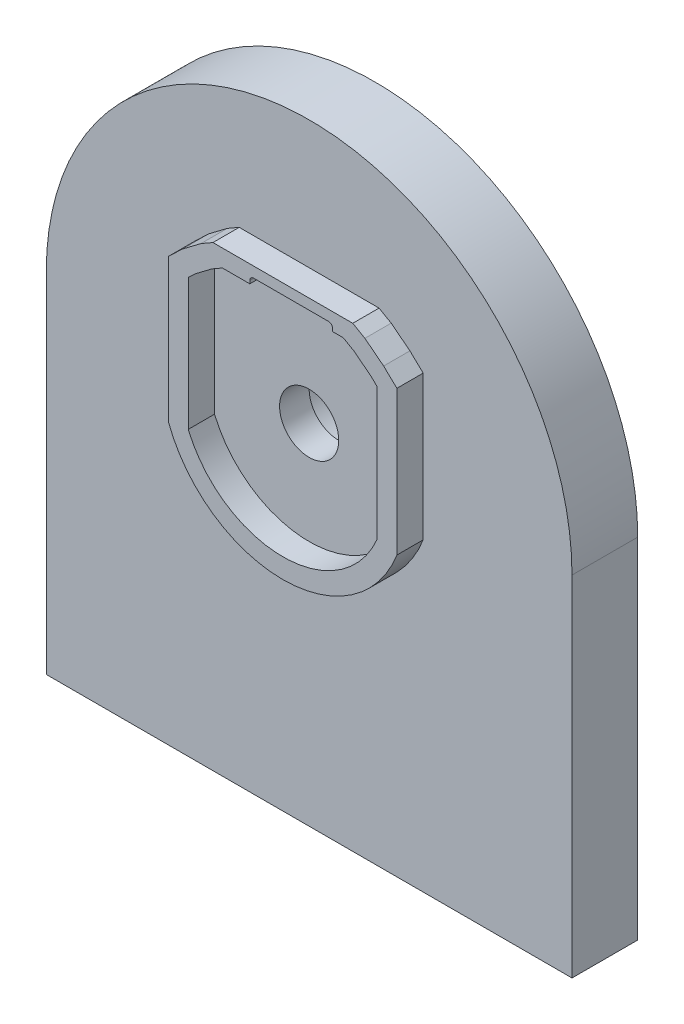
SolidWorks part; units mm, degrees
ref_plane "Front Plane" through (0, 0, 0) normal (0, 0, 1) x (1, 0, 0)
ref_plane "Top Plane" through (0, 0, 0) normal (0, 1, 0) x (1, 0, 0)
ref_plane "Right Plane" through (0, 0, 0) normal (1, 0, 0) x (0, 0, -1)
sketch "Sketch1" plane through (0, 0, 0) normal (0, 0, 1) x (1, 0, 0)
  line L1 (-40, -25) -> (40, -25)
  line L2 (-40, -25) -> (-40, 25)
  line L3 (-40, 25) -> (40, 25)
  line L4 (40, -25) -> (40, 25)
  line L5 (-40, -25) -> (40, 25) construction
  line L6 (-40, 25) -> (40, -25) construction
  point P0 (0, 0)
  dimension "D1" = 80
  dimension "D2" = 50
sketch "Sketch6" plane through (0, 0, 0) normal (0, 0, 1) x (1, 0, 0)
  line L1 (40, -53.1) -> (-40, -53.1)
  line L2 (40, -53.1) -> (40, 53.1)
  line L3 (40, 53.1) -> (-40, 53.1)
  line L4 (-40, -53.1) -> (-40, 53.1)
  line L5 (40, -53.1) -> (-40, 53.1) construction
  line L6 (40, 53.1) -> (-40, -53.1) construction
  point P0 (0, 0)
  point P8 (0, 0)
  point P9 (0, 0)
  point P10 (0, 0)
  dimension "D1" = 80
  dimension "D2" = 106.2
extrude "Boss-Extrude3" add sketch "Sketch6" along normal mid plane 10
sketch "Sketch3" plane through (0, 0, 5) normal (0, 0, 1) x (1, 0, 0)
  line L0 (-14.3953, -5.9991) -> (-14.3953, 14.0234)
  line L1 (-14.3953, 14.0234) -> (-13.3642, 15.0075)
  line L2 (-10.8024, 16.9451) -> (-13.3642, 15.0075)
  line L3 (-10.8024, 16.9451) -> (-9.2024, 17.8657)
  line L4 (-9.2024, 17.8657) -> (-5.0253, 17.8657)
  line L5 (-5.0253, 17.8657) -> (-5.0253, 18.3079)
  line L6 (-4.4301, 18.9031) -> (6.9701, 18.9031)
  line L7 (7.5653, 18.3079) -> (7.5653, 17.8657)
  line L8 (7.5653, 17.8657) -> (9.2024, 17.8657)
  line L9 (9.2024, 17.8657) -> (10.8031, 16.9447)
  line L10 (10.8031, 16.9447) -> (13.371, 14.9429)
  line L11 (13.371, 14.9429) -> (14.3516, 14.0055)
  line L12 (14.3516, 14.0055) -> (14.3516, -6.1027)
  line L13 (-17.3953, -6.5718) -> (-17.3953, 15.3072)
  line L14 (-17.3953, 15.3072) -> (-15.3111, 17.2964)
  line L15 (-12.4619, 19.4514) -> (-15.3111, 17.2964)
  line L16 (-12.4619, 19.4514) -> (-10.6394, 20.5)
  line L17 (10.6394, 20.5) -> (12.4815, 19.4401)
  line L18 (12.4815, 19.4401) -> (15.3347, 17.2159)
  line L19 (15.3347, 17.2159) -> (17.3516, 15.288)
  line L20 (17.3516, 15.288) -> (17.3516, -6.6862)
  line L21 (-10.6394, 20.5) -> (10.6394, 20.5)
  arc A0 (-5.0253, 18.3079) -> (-4.4301, 18.9031) centre (-4.4301, 18.3079) cw
  arc A1 (6.9701, 18.9031) -> (7.5653, 18.3079) centre (6.9701, 18.3079) cw
  arc A2 (-14.3953, -5.9991) -> (14.3516, -6.1027) centre (0, 0) ccw
  arc A3 (-17.3953, -6.5718) -> (17.3516, -6.6862) centre (0, 0) ccw
  dimension "D1" = 15.5953
  dimension "D9" = 0.5952
  dimension "D16" = 0.5952
  dimension "D2" = 5.9991
  dimension "D3" = 20.0224
  dimension "D4" = 20.1082
  dimension "D5" = 1.3566
  dimension "D6" = 3.256
  dimension "D7" = 1.8467
  dimension "D8" = 1.6371
  dimension "D10" = 0.4422
  dimension "D11" = 11.4002
  dimension "D12" = 1.4253
  dimension "D13" = 3.212
  dimension "D14" = 1.846
  dimension "D15" = 4.1771
  dimension "D17" = 0.4422
  dimension "D18" = 0.9373
  dimension "D19" = 2.0018
  dimension "D20" = 0.921
  dimension "D21" = 0.9206
  dimension "D22" = 1.9376
  dimension "D23" = 2.8811
  dimension "D24" = 2.7902
  dimension "D25" = 3.6176
  dimension "D26" = 2.1253
  dimension "D27" = 3.5724
  dimension "D28" = 2.1026
  dimension "D29" = 21.2787
  dimension "D30" = 1.5969
  dimension "D31" = 21.879
  dimension "D32" = 21.9742
extrude "Boss-Extrude2" add sketch "Sketch3" along normal blind 4
sketch "Sketch4" plane through (0, 0, 5) normal (0, 0, 1) x (1, 0, 0)
  line L1 (3.6373, 0) -> (1.8187, 3.15) construction
  line L2 (1.8187, 3.15) -> (-1.8187, 3.15) construction
  line L3 (-1.8187, 3.15) -> (-3.6373, 0) construction
  line L4 (-3.6373, 0) -> (-1.8187, -3.15) construction
  line L5 (-1.8187, -3.15) -> (1.8187, -3.15) construction
  line L6 (1.8187, -3.15) -> (3.6373, 0) construction
  circle A0 centre (0, 0) radius 3.15 construction
  circle A1 centre (0, 0) radius 4.5
  dimension "D2" = 9
  dimension "D1" = 6.3
extrude "Cut-Extrude2" cut sketch "Sketch4" against normal up to next
sketch "Sketch7" plane through (0, 0, -5) normal (0, 0, -1) x (-1, 0, 0)
  circle A0 centre (0, 0) radius 7.75
  point P3 (0, 0)
  dimension "D1" = 15.5
extrude "Cut-Extrude3" cut sketch "Sketch7" against normal blind 5.5
sketch "Sketch8" plane through (0, 0, 0) normal (0, 0, 1) x (1, 0, 0)
  line L0 (-40, 53.1) -> (-40, -53.1) construction
  line L1 (40, -53.1) -> (40, 53.1) construction
  line L2 (-40, 0) -> (-40, 53.1)
  line L3 (-40, 53.1) -> (40, 53.1)
  line L4 (40, 53.1) -> (40, 0)
  arc A0 (-40, 0) -> (40, 0) centre (0, 0) cw
extrude "Cut-Extrude4" cut sketch "Sketch8" along normal up to next (5 mm away) from surface at -5 starting at face at (-7.75, 0, -5)
